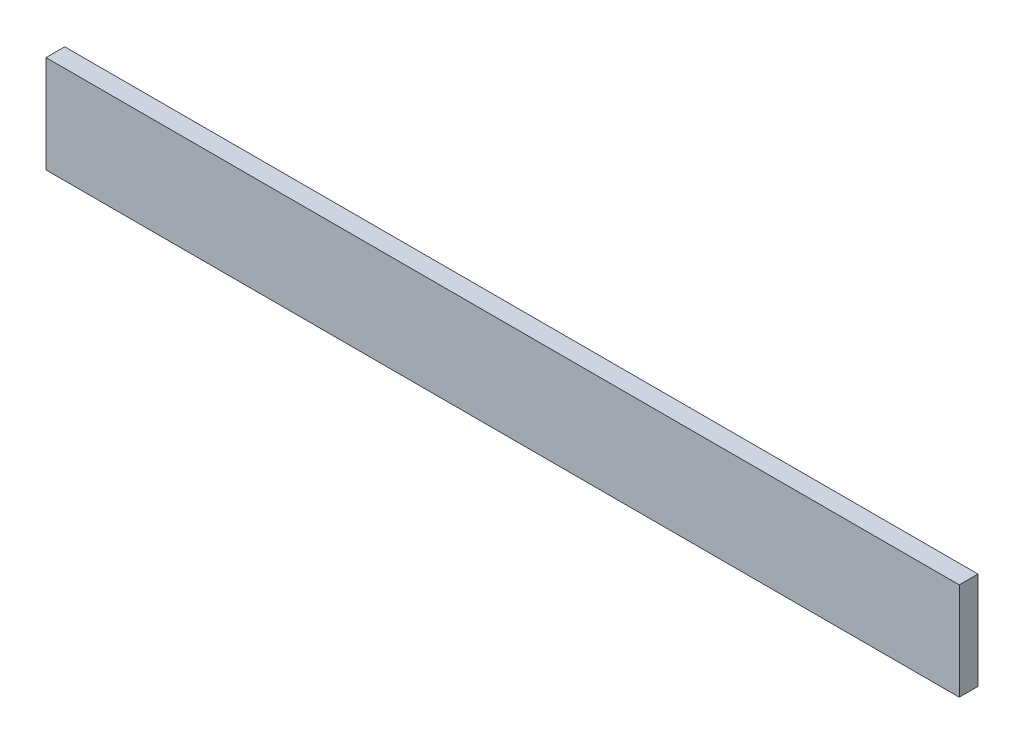
SolidWorks part; units mm, degrees
material "Бальса"
ref_plane "Спереди" through (0, 0, 0) normal (0, 0, 1) x (1, 0, 0)
ref_plane "Сверху" through (0, 0, 0) normal (0, 1, 0) x (1, 0, 0)
ref_plane "Справа" through (0, 0, 0) normal (1, 0, 0) x (0, 0, -1)
sketch "Эскиз1" plane through (0, 0, 0) normal (0, 0, 1) x (1, 0, 0)
  line L1 (0, 0) -> (2440, 0)
  line L2 (0, 0) -> (0, 260)
  line L3 (0, 260) -> (2440, 260)
  line L4 (2440, 0) -> (2440, 260)
  line L5 (2440, 260) -> (2440, 60) construction
  dimension "D1" = 260
extrude "Бобышка-Вытянуть1" add sketch "Эскиз1" along normal blind 50
